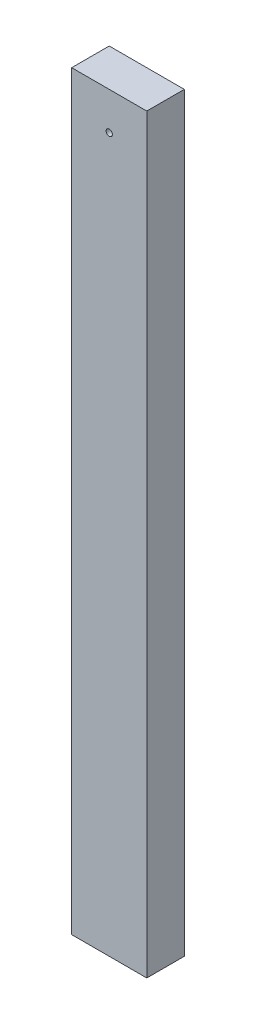
SolidWorks part; units mm, degrees
ref_plane "Front Plane" through (0, 0, 0) normal (0, 0, 1) x (1, 0, 0)
ref_plane "Top Plane" through (0, 0, 0) normal (0, 1, 0) x (1, 0, 0)
ref_plane "Right Plane" through (0, 0, 0) normal (1, 0, 0) x (0, 0, -1)
sketch "Sketch1" plane through (0, 0, 0) normal (0, 1, 0) x (1, 0, 0)
  line L1 (-76.2, -38.1) -> (76.2, -38.1)
  line L2 (-76.2, -38.1) -> (-76.2, 38.1)
  line L3 (-76.2, 38.1) -> (76.2, 38.1)
  line L4 (76.2, -38.1) -> (76.2, 38.1)
  line L5 (-76.2, -38.1) -> (76.2, 38.1) construction
  line L6 (-76.2, 38.1) -> (76.2, -38.1) construction
  point P0 (0, 0)
  dimension "D1" = 152.4
  dimension "D2" = 76.2
extrude "Boss-Extrude1" add sketch "Sketch1" along normal blind 1524
sketch "Sketch2" plane through (0, 0, 38.1) normal (0, 0, 1) x (1, 0, 0)
  line L1 (76.2, 1524) -> (76.2, 0) construction
  circle A0 centre (0, 1447.8) radius 6.35
  dimension "D1" = 12.7
  dimension "D2" = 1447.8
  dimension "D3" = 76.2
extrude "Cut-Extrude1" cut sketch "Sketch2" against normal up to next
